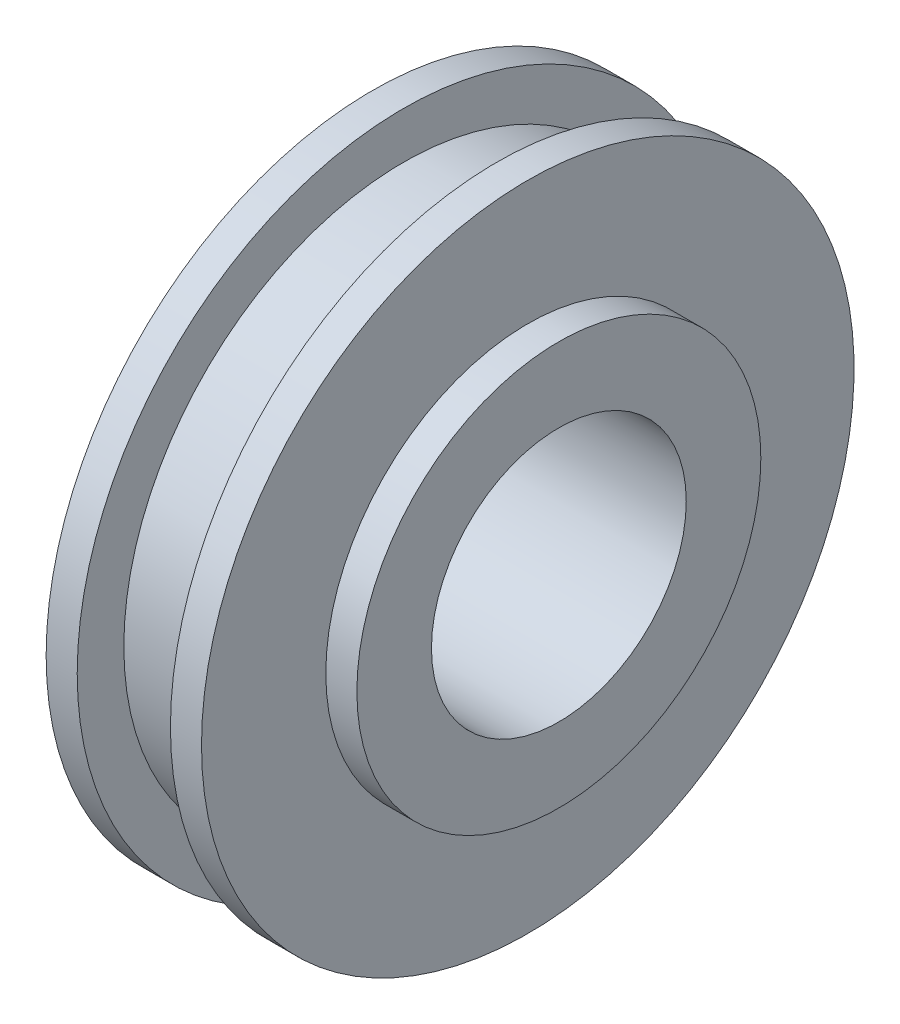
SolidWorks part; units mm, degrees
ref_plane "Front Plane" through (0, 0, 0) normal (0, 0, 1) x (1, 0, 0)
ref_plane "Top Plane" through (0, 0, 0) normal (0, 1, 0) x (1, 0, 0)
ref_plane "Right Plane" through (0, 0, 0) normal (1, 0, 0) x (0, 0, -1)
sketch "Sketch1" plane through (0, 0, 0) normal (0, 0, 1) x (1, 0, 0)
  line L0 (0, 0) -> (5.1881, 0) construction
  line L2 (-5.5, -0.875) -> (-5.5, 10.5) construction
  line L3 (-5.5, 10.5) -> (-0.5, 10.5)
  line L4 (-0.5, 4.1) -> (-0.5, 10.5)
  line L5 (-5.5, 10.5) -> (-5.5, 4.1)
  line L8 (-5.5, 4.1) -> (-0.5, 4.1)
  dimension "D1" = 10.5
  dimension "D2" = 5
  dimension "D5" = 4.1
revolve "Revolve1" add sketch "Sketch1" angle 360 about L0
sketch "Sketch2" plane through (0, 0, 0) normal (0, 0, 1) x (1, 0, 0)
  line L6 (0, 0) -> (5.4705, 0) construction
  line L9 (-0.5, 3.3693) -> (-0.5, 10.5) construction
  line L10 (-0.5, 10.5) -> (-1.5, 10.5) construction
  line L11 (-1.5, 10.5) -> (-1.5, 9) construction
  line L12 (-1.5, 9) -> (-5.5, 9) construction
  line L13 (-5.5, 9) -> (-5.5, 3.3693) construction
  line L14 (-0.5, 10.5) -> (-5.5, 10.5) construction
  line L15 (-0.5, -10.5) -> (-0.5, 10.5) construction
  line L16 (-5.5, 10.5) -> (-5.5, -10.5) construction
  line L17 (-1.5, 9) -> (-1.5, 10.5)
  line L18 (-1.5, 10.5) -> (-4.5, 10.5)
  line L20 (-4.5, 10.5) -> (-4.5, 9)
  line L21 (-4.5, 9) -> (-1.5, 9)
  line L22 (-4.5, 10.5) -> (-5.5, 10.5) construction
  line L23 (-1.5, 10.5) -> (-0.5, 10.5) construction
  dimension "D1" = 9
  dimension "D2" = 3
  dimension "D3" = 1
  dimension "D5" = 1.5
revolve "Cut-Revolve1" cut sketch "Sketch2" angle 360 about L6
sketch "Sketch6" plane through (-0.5, 0, 0) normal (1, 0, 0) x (0, 0, -1)
  circle A0 centre (0, 0) radius 4.1
  circle A1 centre (0, 0) radius 6.5
  circle A2 centre (0, 0) radius 4.1 construction
  dimension "D1" = 13
extrude "Boss-Extrude1" add sketch "Sketch6" along normal blind 1
sketch "Sketch5" plane through (-5.5, 0, 0) normal (-1, 0, 0) x (0, 0, 1)
  text T0 "<b>17</b>\r\n"
  text T1 "v3"
  point P2 (-3.6115, -8.0349)
  point P3 (0, 0)
  point P4 (0, 0)
extrude "Cut-Extrude2" cut sketch "Sketch5" against normal blind 1.5
